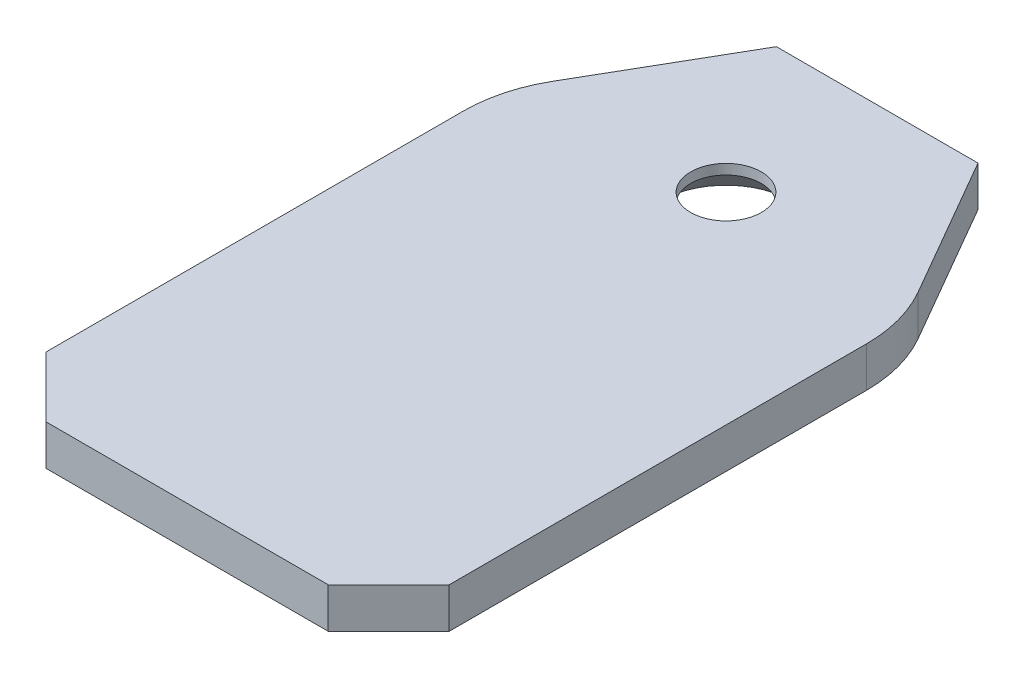
SolidWorks part; units mm, degrees
material "1060 Сплав"
ref_plane "Спереди" through (0, 0, 0) normal (0, 0, 1) x (1, 0, 0)
ref_plane "Сверху" through (0, 0, 0) normal (0, 1, 0) x (1, 0, 0)
ref_plane "Справа" through (0, 0, 0) normal (1, 0, 0) x (0, 0, -1)
sketch "Эскиз2" plane through (0, 0, 0) normal (0, 1, 0) x (1, 0, 0)
  line L0 (-21.1835, -7.6413) -> (-21.1835, -64.1054) construction
  line L2 (-1.1835, -7.6413) -> (-1.1835, -30.8736)
  line L3 (-1.1835, -30.8736) -> (-21.1835, -30.8736)
  line L4 (-21.1835, -7.6413) -> (-21.1835, -30.8736)
  line L6 (-21.1835, -7.1772) -> (-21.1835, -7.6413)
  line L7 (-16.1835, 3.3587) -> (-20.2457, -3.6772)
  line L8 (-6.1835, 3.3587) -> (-16.1835, 3.3587)
  line L9 (-2.1213, -3.6772) -> (-6.1835, 3.3587)
  line L10 (-1.1835, -7.6413) -> (-1.1835, -7.1772)
  line L11 (-21.1835, -7.6413) -> (-1.1835, -7.6413)
  line L12 (-21.1835, -7.1772) -> (-21.1835, -7.6413)
  line L13 (-16.1835, 3.3587) -> (-20.2457, -3.6772)
  line L14 (-6.1835, 3.3587) -> (-16.1835, 3.3587)
  line L15 (-2.1213, -3.6772) -> (-6.1835, 3.3587)
  line L16 (-1.1835, -7.6413) -> (-1.1835, -7.1772)
  arc A2 (-20.2457, -3.6772) -> (-21.1835, -7.1772) centre (-14.1835, -7.1772) ccw
  arc A3 (-1.1835, -7.1772) -> (-2.1213, -3.6772) centre (-8.1835, -7.1772) ccw
  arc A4 (-20.2457, -3.6772) -> (-21.1835, -7.1772) centre (-14.1835, -7.1772) ccw
  arc A5 (-1.1835, -7.1772) -> (-2.1213, -3.6772) centre (-8.1835, -7.1772) ccw
  dimension "D1" = 0
extrude "Бобышка-Вытянуть1" add sketch "Эскиз2" against normal blind 2
sketch "Эскиз3" plane through (0, -2, 0) normal (0, -1, 0) x (1, 0, 0)
  line L0 (-11.1835, -3.3587) -> (-11.1835, 30.8736) construction
  line L1 (-6.1835, -3.3587) -> (-16.1835, -3.3587) construction
  line L2 (-21.1835, 30.8736) -> (-1.1835, 30.8736) construction
  circle A0 centre (-11.1835, 4.1413) radius 1.75
  dimension "D1" = 3.5
  dimension "D2" = 7.5
extrude "Вырез-Вытянуть1" cut sketch "Эскиз3" against normal blind 10
chamfer "Фаска1" distance 3 angle 45 2 edges at (-1.1835, -1, 30.8736) (-21.1835, -1, 30.8736)
chamfer "Фаска2" distance 1.5 angle 45 1 edges at (-11.1835, -2, 2.3913)
